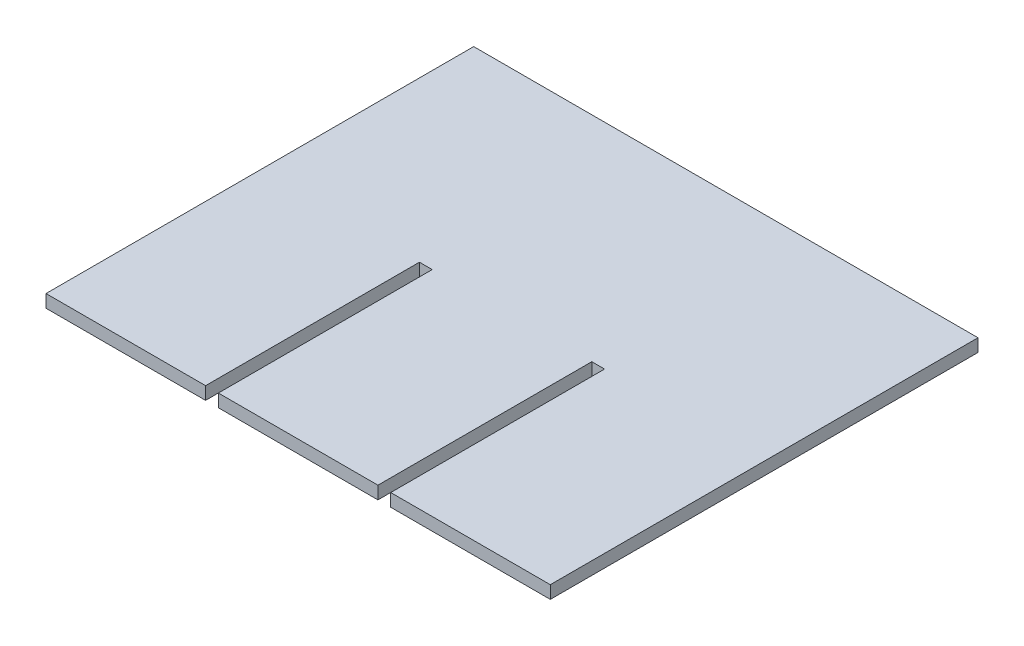
SolidWorks part; units mm, degrees
ref_plane "Front Plane" through (0, 0, 0) normal (0, 0, 1) x (1, 0, 0)
ref_plane "Top Plane" through (0, 0, 0) normal (0, 1, 0) x (1, 0, 0)
ref_plane "Right Plane" through (0, 0, 0) normal (1, 0, 0) x (0, 0, -1)
sketch "Sketch1" plane through (0, 0, 0) normal (0, 1, 0) x (1, 0, 0)
  line L1 (39.5, -33.5) -> (-39.5, -33.5)
  line L2 (39.5, -33.5) -> (39.5, 33.5)
  line L3 (39.5, 33.5) -> (-39.5, 33.5)
  line L4 (-39.5, -33.5) -> (-39.5, 33.5)
  line L5 (39.5, -33.5) -> (-39.5, 33.5) construction
  line L6 (39.5, 33.5) -> (-39.5, -33.5) construction
  point P0 (0, 0)
  dimension "D1" = 79
  dimension "D2" = 67
extrude "Boss-Extrude1" add sketch "Sketch1" along normal blind 2
sketch "Sketch2" plane through (0, 2, 0) normal (0, 1, 0) x (1, 0, 0)
  line L0 (-39.5, -33.5) -> (-14.5, -33.5)
  line L1 (-39.5, -33.5) -> (39.5, -33.5) construction
  line L2 (-14.5, -33.5) -> (-14.5, 0)
  line L3 (-14.5, 0) -> (-12.5, 0)
  line L4 (-12.5, 0) -> (-12.5, -33.5)
  line L5 (-12.5, -33.5) -> (-14.5, -33.5)
  line L6 (0, 14.4325) -> (0, -29.5422) construction
  line L7 (12.5, -33.5) -> (14.5, -33.5)
  line L8 (14.5, 0) -> (12.5, 0)
  line L9 (12.5, 0) -> (12.5, -33.5)
  line L10 (14.5, -33.5) -> (14.5, 0)
  dimension "D1" = 25
  dimension "D2" = 33.5
  dimension "D3" = 2
  dimension "D4" = 12.5
extrude "Cut-Extrude1" cut sketch "Sketch2" against normal through all contours L9 L7 L10 L8 | L2 L3 L4 L5
